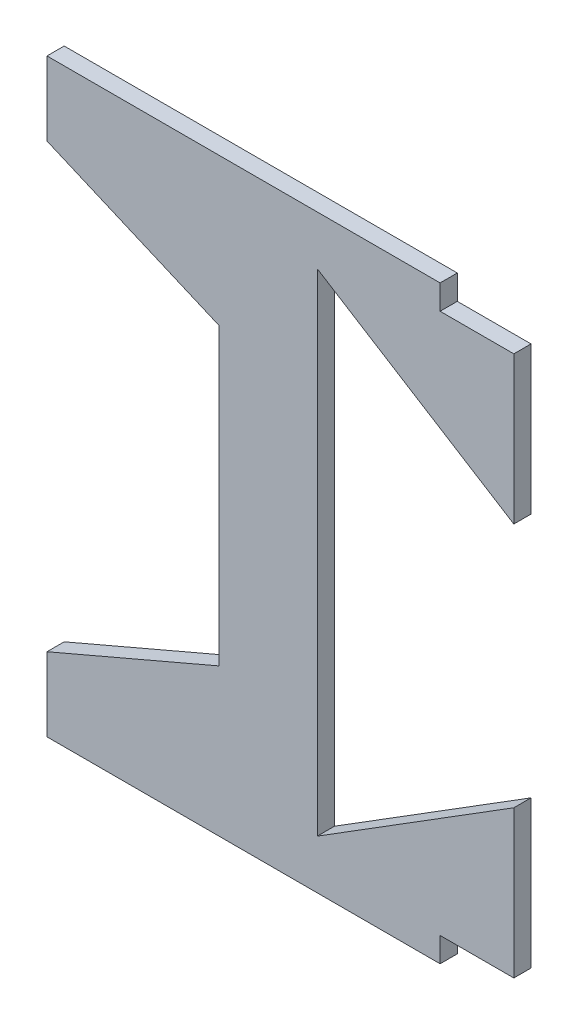
SolidWorks part; units mm, degrees
ref_plane "Ebene vorne" through (0, 0, 0) normal (0, 0, 1) x (1, 0, 0)
ref_plane "Ebene oben" through (0, 0, 0) normal (0, 1, 0) x (1, 0, 0)
ref_plane "Ebene rechts" through (0, 0, 0) normal (1, 0, 0) x (0, 0, -1)
sketch "Skizze1" plane through (0, 0, 0) normal (0, 0, 1) x (1, 0, 0)
  line L0 (0, 0) -> (110.9056, 0) construction
  line L1 (30.2855, 30) -> (30.2855, -30)
  line L2 (30.2855, -30) -> (-4.7145, -45)
  line L3 (-4.7145, -45) -> (-4.7145, -60)
  line L4 (-4.7145, -60) -> (75.2855, -60)
  line L5 (75.2855, -60) -> (75.2855, -55)
  line L6 (75.2855, -55) -> (90.2855, -55)
  line L7 (90.2855, -55) -> (90.2855, -25)
  line L8 (90.2855, -25) -> (50.2855, -50)
  line L9 (50.2855, -50) -> (50.2855, 50)
  line L10 (90.2855, 25) -> (50.2855, 50)
  line L11 (90.2855, 55) -> (90.2855, 25)
  line L12 (75.2855, 55) -> (90.2855, 55)
  line L13 (75.2855, 60) -> (75.2855, 55)
  line L14 (-4.7145, 60) -> (75.2855, 60)
  line L15 (-4.7145, 45) -> (-4.7145, 60)
  line L16 (30.2855, 30) -> (-4.7145, 45)
  point P14 (50.2855, 0)
  point P21 (30.2855, 0)
  dimension "D1" = 95
  dimension "D2" = 120
  dimension "D3" = 90
  dimension "D4" = 60
  dimension "D5" = 50
  dimension "D6" = 100
  dimension "D7" = 15
  dimension "D8" = 40
  dimension "D9" = 110
  dimension "D10" = 35
extrude "Aufsatz-Linear austragen1" add sketch "Skizze1" along normal blind 3.5
